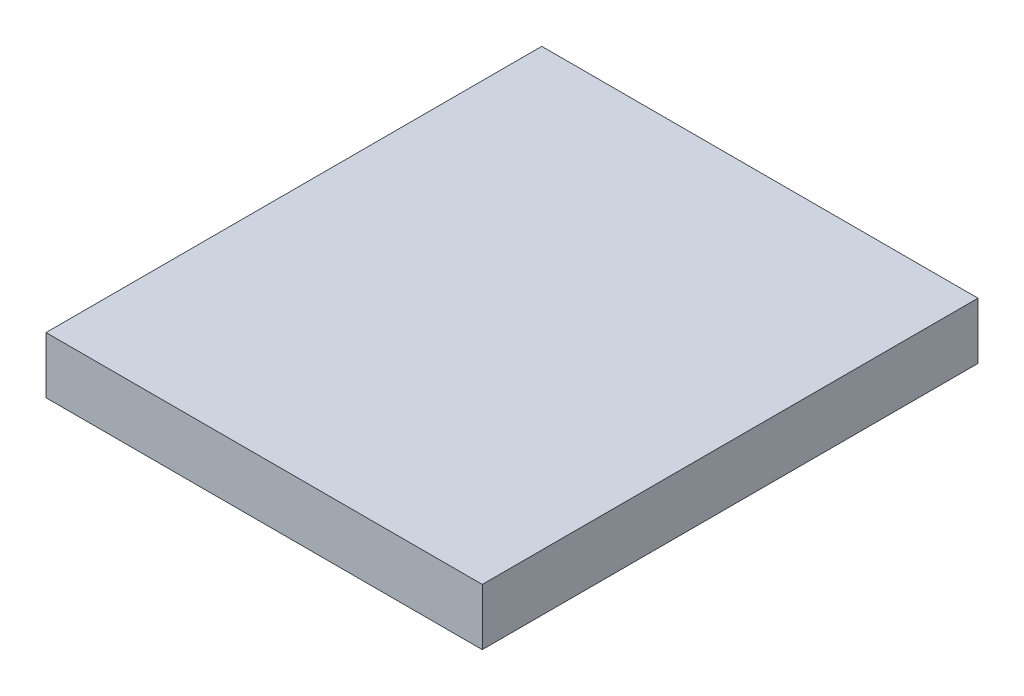
SolidWorks part; units mm, degrees
ref_plane "Front Plane" through (0, 0, 0) normal (0, 0, 1) x (1, 0, 0)
ref_plane "Top Plane" through (0, 0, 0) normal (0, 1, 0) x (1, 0, 0)
ref_plane "Right Plane" through (0, 0, 0) normal (1, 0, 0) x (0, 0, -1)
sketch "Sketch1" plane through (0, 0, 0) normal (0, 1, 0) x (1, 0, 0)
  line L1 (0, 25) -> (22, 25)
  line L2 (0, 25) -> (0, 0)
  line L3 (0, 0) -> (22, 0)
  line L4 (22, 25) -> (22, 0)
  point P6 (22, 12.5)
  dimension "D1" = 22
  dimension "D2" = 25
extrude "Boss-Extrude1" add sketch "Sketch1" along normal blind 2.85
equation "\"acryllic\"= 2.85mm"
equation "\"wall\"= 1.5mm"
equation "\"laserOD\"= 6.34mm + 2 * \"wall\""
equation "\"tankL\"= 7.5cm"
equation "\"tankW\"= 5cm"
equation "\"edgeClr\"= \"tankW\" / \"edgeClr_a\""
equation "\"edgeClr_a\"= 2'edgeClr_a determines how big turret edge clearance is"
equation "\"acryllicSkirt\"= .5mm"
equation "\"D2@Sketch1\"=\"tankL\"/3"
equation "\"D1@Sketch1\"=\"tankW\"-\"edgeClr\"-2*\"wall\""
equation "\"D1@Boss-Extrude1\"=\"acryllic\""
